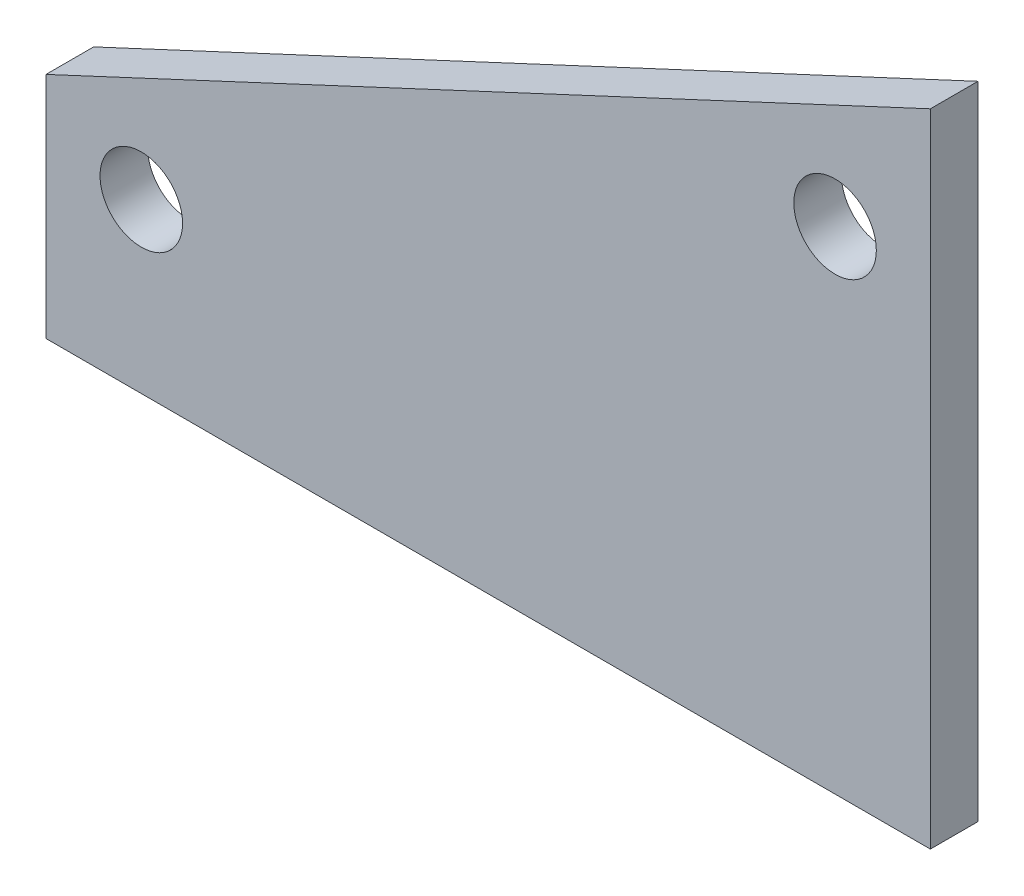
SolidWorks part; units mm, degrees
material "Plain Carbon Steel"
ref_plane "Front Plane" through (0, 0, 0) normal (0, 0, 1) x (1, 0, 0)
ref_plane "Top Plane" through (0, 0, 0) normal (0, 1, 0) x (1, 0, 0)
ref_plane "Right Plane" through (0, 0, 0) normal (1, 0, 0) x (0, 0, -1)
sketch "Sketch1" plane through (0, 0, 0) normal (0, 0, 1) x (1, 0, 0)
  line L0 (-181.0328, -160.8785) -> (-181.0328, -176.1211)
  line L1 (-181.0328, -176.1211) -> (-122.1048, -176.1211)
  line L2 (-122.1048, -176.1211) -> (-122.1048, -133.3999)
  line L3 (-122.1048, -133.3999) -> (-181.0328, -160.8785)
  circle A0 centre (-128.4548, -143.3703) radius 2.75
  circle A1 centre (-174.6828, -164.9239) radius 2.75
extrude "Boss-Extrude1" add sketch "Sketch1" against normal blind 3.175 contours L2 L3 L0 L1 A1 A0
